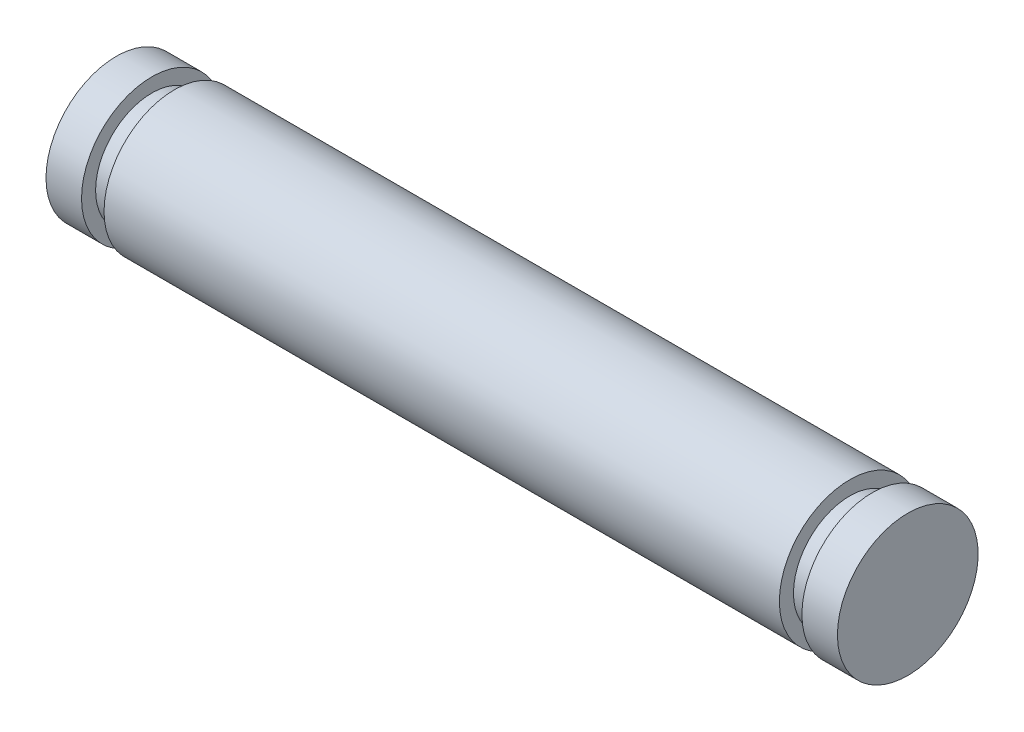
SolidWorks part; units mm, degrees
material "Plain Carbon Steel"
ref_plane "Front Plane" through (0, 0, 0) normal (0, 0, 1) x (1, 0, 0)
ref_plane "Top Plane" through (0, 0, 0) normal (0, 1, 0) x (1, 0, 0)
ref_plane "Right Plane" through (0, 0, 0) normal (1, 0, 0) x (0, 0, -1)
sketch "Sketch1" plane through (0, 0, 0) normal (1, 0, 0) x (0, 0, -1)
  circle A0 centre (0, 0) radius 2
  dimension "D1" = 4
extrude "Boss-Extrude1" add sketch "Sketch1" along normal mid plane 22.5
ref_axis "Axis1" through (-12.375, 0, 0) along (1, 0, 0)
sketch "Sketch3" plane through (0, 0, 0) normal (0, 1, 0) x (1, 0, 0)
  line L0 (11.25, 2) -> (-11.25, 2) construction
  line L1 (-10.24, 2) -> (-9.6, 2)
  line L2 (-10.24, 2) -> (-10.24, 1.6)
  line L3 (-10.24, 1.6) -> (-9.6, 1.6)
  line L4 (-9.6, 2) -> (-9.6, 1.6)
  line L5 (-12.375, 0) -> (12.375, 0) construction
  dimension "D1" = 0.64
  dimension "D2" = 1.6
  dimension "D3" = 9.6
revolve "Cut-Revolve1" cut sketch "Sketch3" angle 360 about axis through (-12.375, 0, 0) along (1, 0, 0)
mirror "Mirror1" about plane through (0, 0, 0) normal (1, 0, 0) of "Cut-Revolve1"
